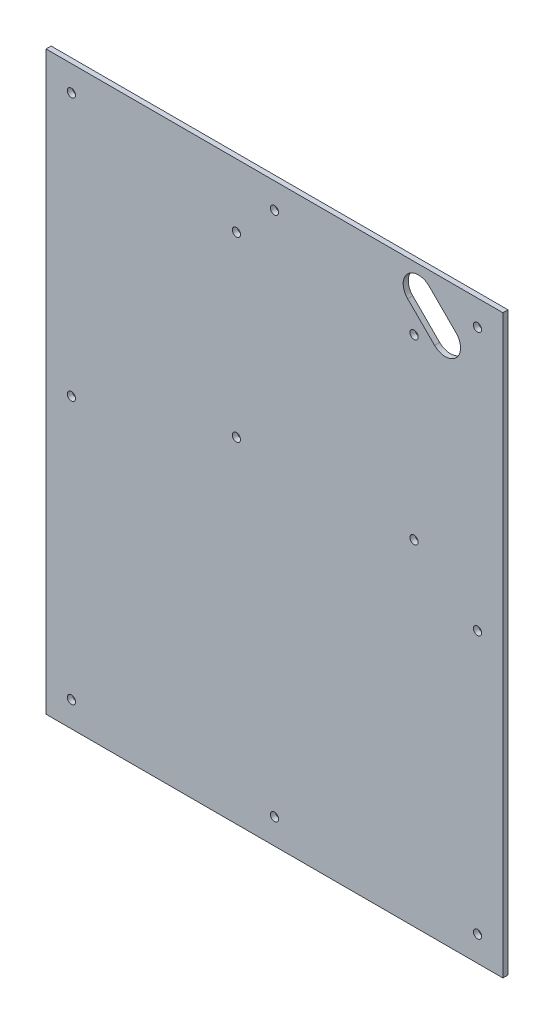
SolidWorks part; units mm, degrees
material "C-玻璃纤维"
ref_plane "前视基准面" through (0, 0, 0) normal (0, 0, 1) x (1, 0, 0)
ref_plane "上视基准面" through (0, 0, 0) normal (0, 1, 0) x (1, 0, 0)
ref_plane "右视基准面" through (0, 0, 0) normal (1, 0, 0) x (0, 0, -1)
sketch "草图1" plane through (0, 0, 0) normal (0, 0, 1) x (1, 0, 0)
  line L1 (90, -113.5) -> (-90, -113.5)
  line L2 (90, -113.5) -> (90, 113.5)
  line L3 (90, 113.5) -> (-90, 113.5)
  line L4 (-90, -113.5) -> (-90, 113.5)
  line L5 (90, -113.5) -> (-90, 113.5) construction
  line L6 (90, 113.5) -> (-90, -113.5) construction
  line L7 (55, 18.5) -> (-15, 18.5) construction
  line L8 (55, 18.5) -> (55, 88.5) construction
  line L9 (55, 88.5) -> (-15, 88.5) construction
  line L10 (-15, 18.5) -> (-15, 88.5) construction
  line L11 (55, 18.5) -> (-15, 88.5) construction
  line L12 (55, 88.5) -> (-15, 18.5) construction
  line L13 (80, -103.5) -> (-80, -103.5) construction
  line L14 (80, -103.5) -> (80, 103.5) construction
  line L15 (80, 103.5) -> (-80, 103.5) construction
  line L16 (-80, -103.5) -> (-80, 103.5) construction
  line L17 (80, -103.5) -> (-80, 103.5) construction
  line L18 (80, 103.5) -> (-80, -103.5) construction
  line L20 (63.0761, 88.9091) -> (52.4695, 99.5158)
  line L21 (60.9548, 108.001) -> (71.5614, 97.3944)
  line L22 (55, 88.5) -> (66.2581, 102.6977) construction
  circle A0 centre (-15, 88.5) radius 1.625
  circle A1 centre (55, 88.5) radius 1.625
  circle A2 centre (55, 18.5) radius 1.625
  circle A3 centre (-15, 18.5) radius 1.625
  circle A4 centre (-80, 103.5) radius 1.625
  circle A5 centre (0, 103.5) radius 1.625
  circle A6 centre (80, 103.5) radius 1.625
  circle A7 centre (80, -103.5) radius 1.625
  circle A8 centre (0, -103.5) radius 1.625
  circle A9 centre (-80, -103.5) radius 1.625
  circle A10 centre (80, 0) radius 1.625
  circle A11 centre (-80, 0) radius 1.625
  arc A14 (52.4695, 99.5158) -> (60.9548, 108.001) centre (56.7122, 103.7584) cw
  arc A15 (71.5614, 97.3944) -> (63.0761, 88.9091) centre (67.3188, 93.1518) cw
  point P0 (0, 0)
  point P6 (20, 53.5)
  point P15 (0, 0)
  point P44 (66.2581, 102.6977)
  dimension "D7" = 3.25
  dimension "D15" = 6
  dimension "D1" = 180
  dimension "D2" = 227
  dimension "D3" = 70
  dimension "D4" = 70
  dimension "D5" = 25
  dimension "D6" = 25
  dimension "D8" = 20
  dimension "D9" = 10
  dimension "D13" = 45
  dimension "D14" = 15
  dimension "D16" = 18
extrude "凸台-拉伸1" add sketch "草图1" along normal blind 2
